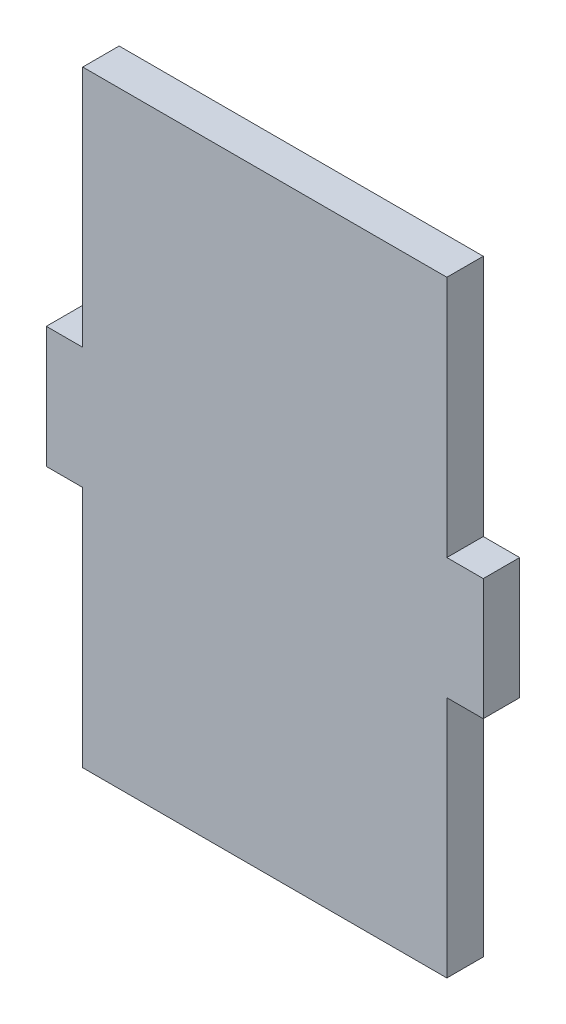
SolidWorks part; units mm, degrees
ref_plane "Front Plane" through (0, 0, 0) normal (0, 0, 1) x (1, 0, 0)
ref_plane "Top Plane" through (0, 0, 0) normal (0, 1, 0) x (1, 0, 0)
ref_plane "Right Plane" through (0, 0, 0) normal (1, 0, 0) x (0, 0, -1)
sketch "Sketch1" plane through (0, 0, 0) normal (0, 0, 1) x (1, 0, 0)
  line L0 (-15, -5) -> (-18, -5)
  line L1 (15, -25) -> (-15, -25)
  line L2 (15, -25) -> (15, -5)
  line L3 (15, 25) -> (-15, 25)
  line L4 (-15, -25) -> (-15, -5)
  line L5 (15, -25) -> (-15, 25) construction
  line L6 (15, 25) -> (-15, -25) construction
  line L7 (-18, -5) -> (-18, 5)
  line L8 (-18, 5) -> (-15, 5)
  line L9 (15, 5) -> (18, 5)
  line L10 (18, 5) -> (18, -5)
  line L11 (18, -5) -> (15, -5)
  line L12 (-15, 5) -> (-15, 25)
  line L13 (15, 5) -> (15, 25)
  point P0 (0, 0)
  dimension "D1" = 30
  dimension "D2" = 50
  dimension "D3" = 10
  dimension "D4" = 3
  dimension "D5" = 20
  dimension "D6" = 10
  dimension "D7" = 3
  dimension "D8" = 20
extrude "Boss-Extrude1" add sketch "Sketch1" along normal blind 3
